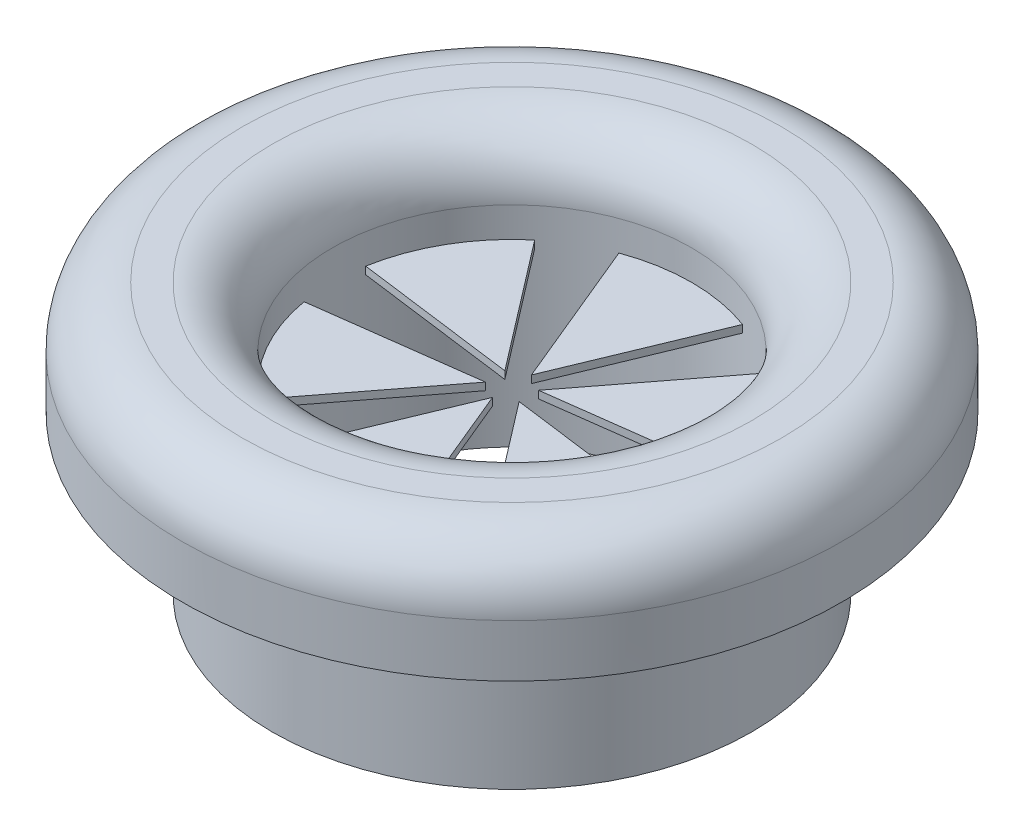
SolidWorks part; units mm, degrees
material "1060 Alloy"
ref_plane "Front Plane" through (0, 0, 0) normal (0, 0, 1) x (1, 0, 0)
ref_plane "Top Plane" through (0, 0, 0) normal (0, 1, 0) x (1, 0, 0)
ref_plane "Right Plane" through (0, 0, 0) normal (1, 0, 0) x (0, 0, -1)
sketch "Sketch1" plane through (0, 0, 0) normal (0, 1, 0) x (1, 0, 0)
  circle A0 centre (0, 0) radius 8
  dimension "D1" = 16
extrude "Boss-Extrude1" add sketch "Sketch1" along normal blind 5
sketch "Sketch2" plane through (0, 5, 0) normal (0, 1, 0) x (1, 0, 0)
  circle A0 centre (0, 0) radius 11
  dimension "D1" = 22
extrude "Boss-Extrude2" add sketch "Sketch2" along normal blind 4
sketch "Sketch3" plane through (0, 9, 0) normal (0, 1, 0) x (1, 0, 0)
  circle A0 centre (0, 0) radius 6
  dimension "D1" = 12
extrude "Cut-Extrude1" cut sketch "Sketch3" against normal through all
sketch "Sketch4" plane through (0, 0, 0) normal (0, -1, 0) x (1, 0, 0)
  line L0 (0, 6) -> (0, 0) construction
  line L1 (0, 0.65) -> (-2.0643, 5.6337)
  line L2 (0, 0.65) -> (2.0643, 5.6337)
  line L3 (0.5629, 0.325) -> (3.8468, 4.6046)
  line L4 (0.5629, 0.325) -> (5.9111, 1.0291)
  line L5 (0.5629, -0.325) -> (5.9111, -1.0291)
  line L6 (0.5629, -0.325) -> (3.8468, -4.6046)
  line L7 (0, -0.65) -> (2.0643, -5.6337)
  line L8 (0, -0.65) -> (-2.0643, -5.6337)
  line L9 (-0.5629, -0.325) -> (-3.8468, -4.6046)
  line L10 (-0.5629, -0.325) -> (-5.9111, -1.0291)
  line L11 (-0.5629, 0.325) -> (-5.9111, 1.0291)
  line L12 (-0.5629, 0.325) -> (-3.8468, 4.6046)
  circle A0 centre (0, 0) radius 6 construction
  arc A1 (-2.0643, 5.6337) -> (2.0643, 5.6337) centre (0, 0) cw
  arc A2 (3.8468, 4.6046) -> (5.9111, 1.0291) centre (0, 0) cw
  arc A3 (5.9111, -1.0291) -> (3.8468, -4.6046) centre (0, 0) cw
  arc A4 (2.0643, -5.6337) -> (-2.0643, -5.6337) centre (0, 0) cw
  arc A5 (-3.8468, -4.6046) -> (-5.9111, -1.0291) centre (0, 0) cw
  arc A6 (-5.9111, 1.0291) -> (-3.8468, 4.6046) centre (0, 0) cw
  point P26 (0, 0)
  dimension "D1" = 45
  dimension "D2" = 0.65
  dimension "D3" = 6
extrude "Boss-Extrude3" add sketch "Sketch4" along normal blind 0.25 from offset 6 offset against normal yes
sketch "Sketch5" plane through (0, 5, 0) normal (0, -1, 0) x (1, 0, 0)
  circle A0 centre (0, 0) radius 10
  circle A1 centre (0, 0) radius 11
  circle A2 centre (0, 0) radius 11
  dimension "D1" = 0
  dimension "D2" = 1
extrude "Cut-Extrude2" cut sketch "Sketch5" against normal blind 0.25
fillet "Fillet1" radius 2 2 edges at (0, 9, 11) (0, 9, 6)
